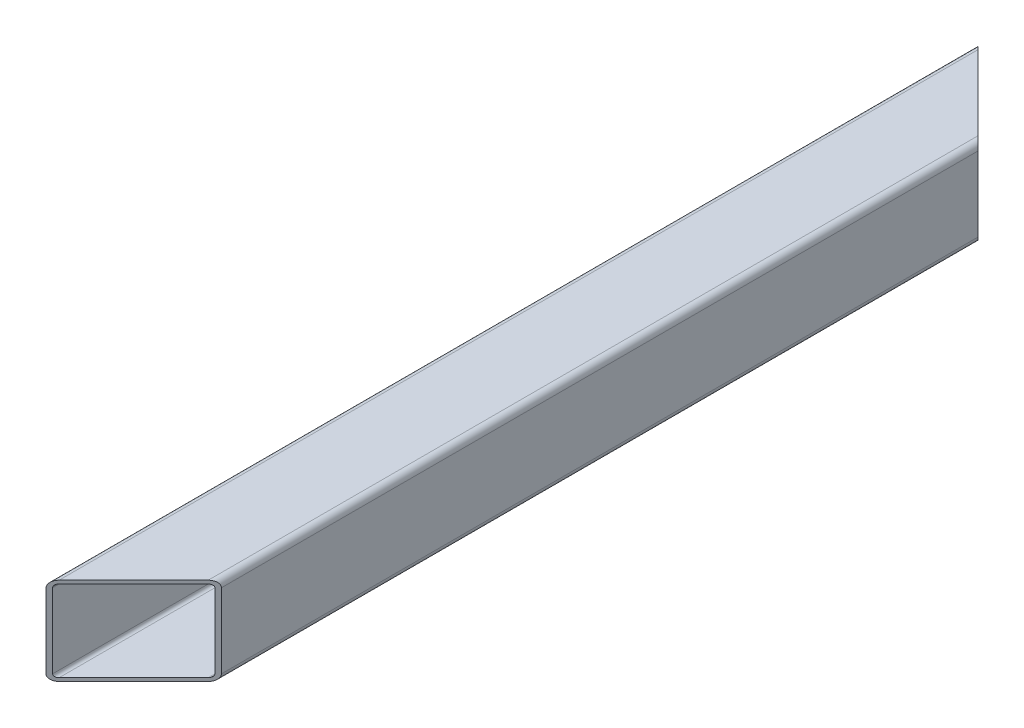
SolidWorks part; units mm, degrees
material "1.0038 (S235JRG2)"
ref_plane "Ebene vorne" through (0, 0, 0) normal (0, 0, 1) x (1, 0, 0)
ref_plane "Ebene oben" through (0, 0, 0) normal (0, 1, 0) x (1, 0, 0)
ref_plane "Ebene rechts" through (0, 0, 0) normal (1, 0, 0) x (0, 0, -1)
sketch "Skizze1" plane through (0, 0, 0) normal (0, 0, 1) x (1, 0, 0)
  line L0 (0, 0) -> (0, 67.8952) construction
  line L1 (-34, 40) -> (34, 40)
  line L2 (0, 0) -> (65.406, 0) construction
  line L3 (40, 34) -> (40, -34)
  line L4 (-40, 34) -> (-40, -34)
  line L5 (-34, -40) -> (34, -40)
  line L6 (-37, 34) -> (-37, -34)
  line L7 (-34, -37) -> (34, -37)
  line L8 (37, 34) -> (37, -34)
  line L9 (-34, 37) -> (34, 37)
  arc A0 (34, 40) -> (40, 34) centre (34, 34) cw
  arc A1 (-34, 40) -> (-40, 34) centre (-34, 34) ccw
  arc A2 (-34, -40) -> (-40, -34) centre (-34, -34) cw
  arc A3 (34, -40) -> (40, -34) centre (34, -34) ccw
  arc A4 (-34, -37) -> (-37, -34) centre (-34, -34) cw
  arc A5 (34, -37) -> (37, -34) centre (34, -34) ccw
  arc A6 (34, 37) -> (37, 34) centre (34, 34) cw
  arc A7 (-34, 37) -> (-37, 34) centre (-34, 34) ccw
  point P12 (40, 0)
  point P13 (0, 40)
  point P19 (-40, 0)
  dimension "D1" = 6
  dimension "D3" = 80
  dimension "D4" = 80
  dimension "D2" = 3
extrude "Aufsatz-Linear austragen1" add sketch "Skizze1" along normal mid plane 850
sketch "Skizze2" plane through (0, 40, 0) normal (0, 1, 0) x (1, 0, 0)
  line L0 (0, 0) -> (147.8944, 0) construction
  line L1 (-40, 425) -> (40, 425)
  line L2 (40, 425) -> (40, 345)
  line L3 (40, 345) -> (-40, 425)
  line L4 (34, 425) -> (-34, 425) construction
  line L5 (-40, -425) -> (-40, 425) construction
  line L6 (40, -425) -> (40, 425) construction
  line L7 (40, -345) -> (-40, -425)
  line L8 (40, -425) -> (40, -345)
  line L9 (-40, -425) -> (40, -425)
  dimension "D1" = 45
extrude "Schnitt-Linear austragen1" cut sketch "Skizze2" against normal blind 140
